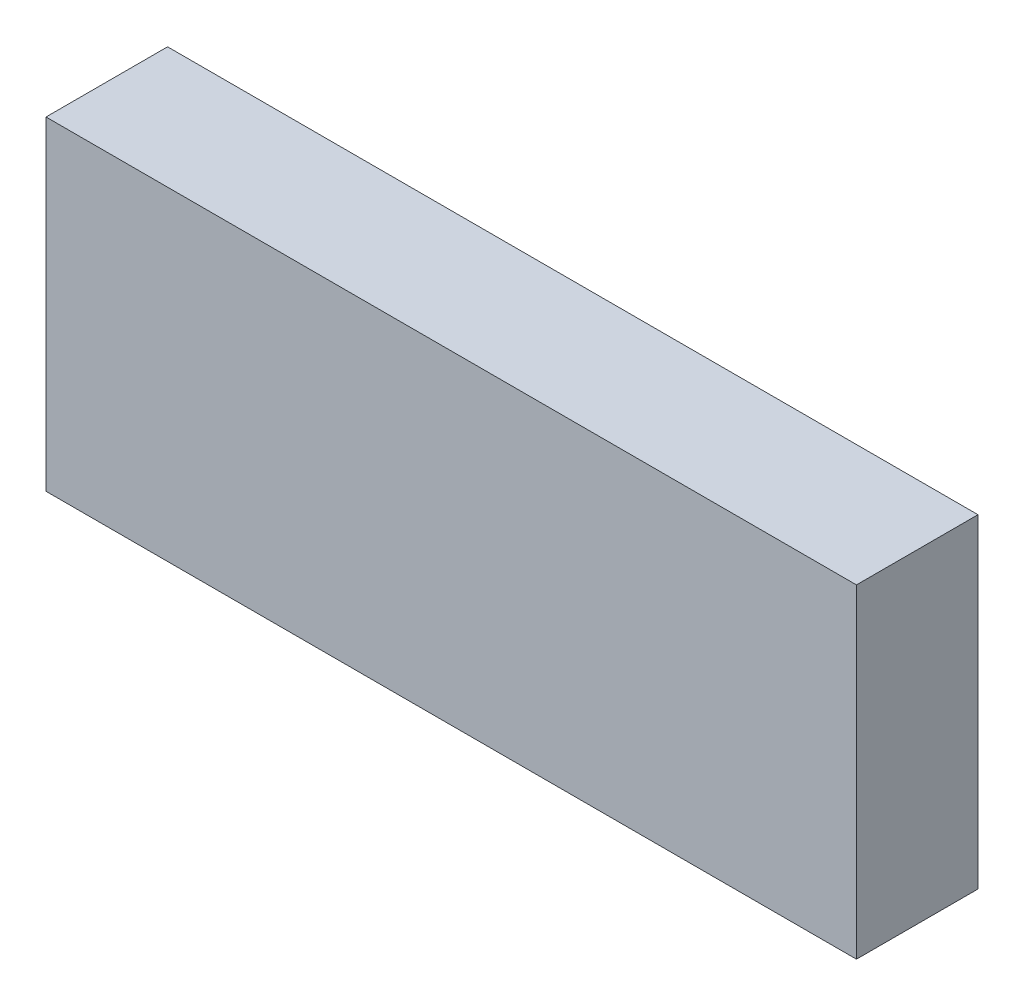
SolidWorks part; units mm, degrees
ref_plane "前视基准面" through (0, 0, 0) normal (0, 0, 1) x (1, 0, 0)
ref_plane "上视基准面" through (0, 0, 0) normal (0, 1, 0) x (1, 0, 0)
ref_plane "右视基准面" through (0, 0, 0) normal (1, 0, 0) x (0, 0, -1)
sketch "草图1" plane through (0, 0, 0) normal (0, 0, 1) x (1, 0, 0)
  line L1 (-100, 40) -> (100, 40)
  line L2 (-100, 40) -> (-100, -40)
  line L3 (-100, -40) -> (100, -40)
  line L4 (100, 40) -> (100, -40)
  line L5 (-100, 40) -> (100, -40) construction
  line L6 (-100, -40) -> (100, 40) construction
  point P0 (0, 0)
  dimension "D1" = 80
  dimension "D2" = 200
extrude "凸台-拉伸1" add sketch "草图1" along normal mid plane 30
equation "\"零件重量\"= \"SW-质量\""
